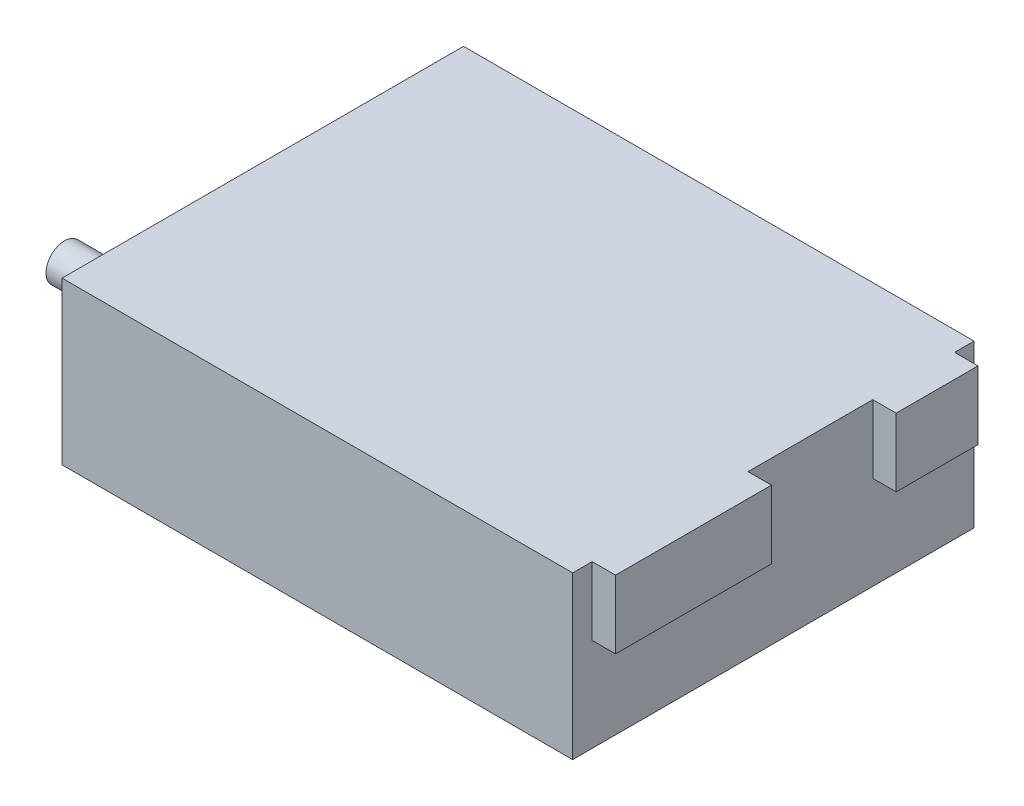
SolidWorks part; units mm, degrees
ref_plane "Front Plane" through (0, 0, 0) normal (0, 0, 1) x (1, 0, 0)
ref_plane "Top Plane" through (0, 0, 0) normal (0, 1, 0) x (1, 0, 0)
ref_plane "Right Plane" through (0, 0, 0) normal (1, 0, 0) x (0, 0, -1)
sketch "Sketch1" plane through (0, 0, 0) normal (0, 1, 0) x (1, 0, 0)
  line L1 (-13.1, 10.3) -> (13.1, 10.3)
  line L2 (-13.1, 10.3) -> (-13.1, -10.3)
  line L3 (-13.1, -10.3) -> (13.1, -10.3)
  line L4 (13.1, 10.3) -> (13.1, -10.3)
  line L5 (-13.1, 10.3) -> (13.1, -10.3) construction
  line L6 (-13.1, -10.3) -> (13.1, 10.3) construction
  point P0 (0, 0)
  dimension "D1" = 26.2
  dimension "D2" = 20.6
extrude "Boss-Extrude1" add sketch "Sketch1" along normal blind 8.3
sketch "Sketch2" plane through (13.1, 0, 0) normal (1, 0, 0) x (0, 0, -1)
  line L0 (-10.3, 8.3) -> (10.3, 8.3) construction
  line L1 (-9.3, 8.3) -> (-1.3, 8.3)
  line L2 (-9.3, 8.3) -> (-9.3, 4.8)
  line L3 (-9.3, 4.8) -> (-1.3, 4.8)
  line L4 (-1.3, 8.3) -> (-1.3, 4.8)
  line L5 (-10.3, 8.3) -> (-10.3, 0) construction
  line L6 (10.3, 8.3) -> (10.3, 0) construction
  line L7 (9.3, 8.3) -> (5.1, 8.3)
  line L8 (9.3, 8.3) -> (9.3, 4.8)
  line L9 (9.3, 4.8) -> (5.1, 4.8)
  line L10 (5.1, 8.3) -> (5.1, 4.8)
  dimension "D1" = 8
  dimension "D2" = 3.5
  dimension "D3" = 1
  dimension "D4" = 4.2
  dimension "D5" = 1
extrude "Boss-Extrude2" add sketch "Sketch2" along normal blind 1.2
sketch "Sketch3" plane through (-13.1, 0, 0) normal (-1, 0, 0) x (0, 0, 1)
  circle A0 centre (5.1748, 3.9453) radius 0.95
  point P2 (5.1748, 3.9453)
  dimension "D1" = 1.9
extrude "Boss-Extrude3" add sketch "Sketch3" along normal blind 5
